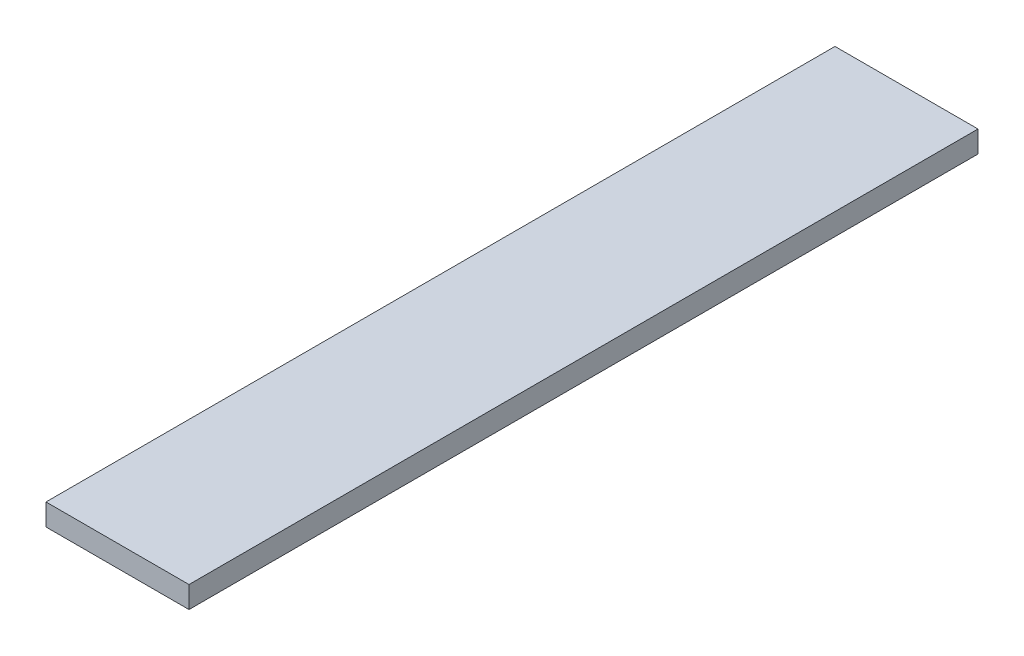
SolidWorks part; units mm, degrees
material "Pine"
ref_plane "Ön Düzlem" through (0, 0, 0) normal (0, 0, 1) x (1, 0, 0)
ref_plane "Üst Düzlem" through (0, 0, 0) normal (0, 1, 0) x (1, 0, 0)
ref_plane "Sağ Düzlem" through (0, 0, 0) normal (1, 0, 0) x (0, 0, -1)
sketch "Çizim1" plane through (0, 0, 0) normal (0, 1, 0) x (1, 0, 0)
  line L1 (-72.5, -400) -> (72.5, -400)
  line L2 (-72.5, -400) -> (-72.5, 400)
  line L3 (-72.5, 400) -> (72.5, 400)
  line L4 (72.5, -400) -> (72.5, 400)
  line L5 (-72.5, -400) -> (72.5, 400) construction
  line L6 (-72.5, 400) -> (72.5, -400) construction
  point P0 (0, 0)
  dimension "D1" = 800
  dimension "D2" = 145
extrude "Yükseklik-Ekstrüzyon1" add sketch "Çizim1" along normal blind 22
